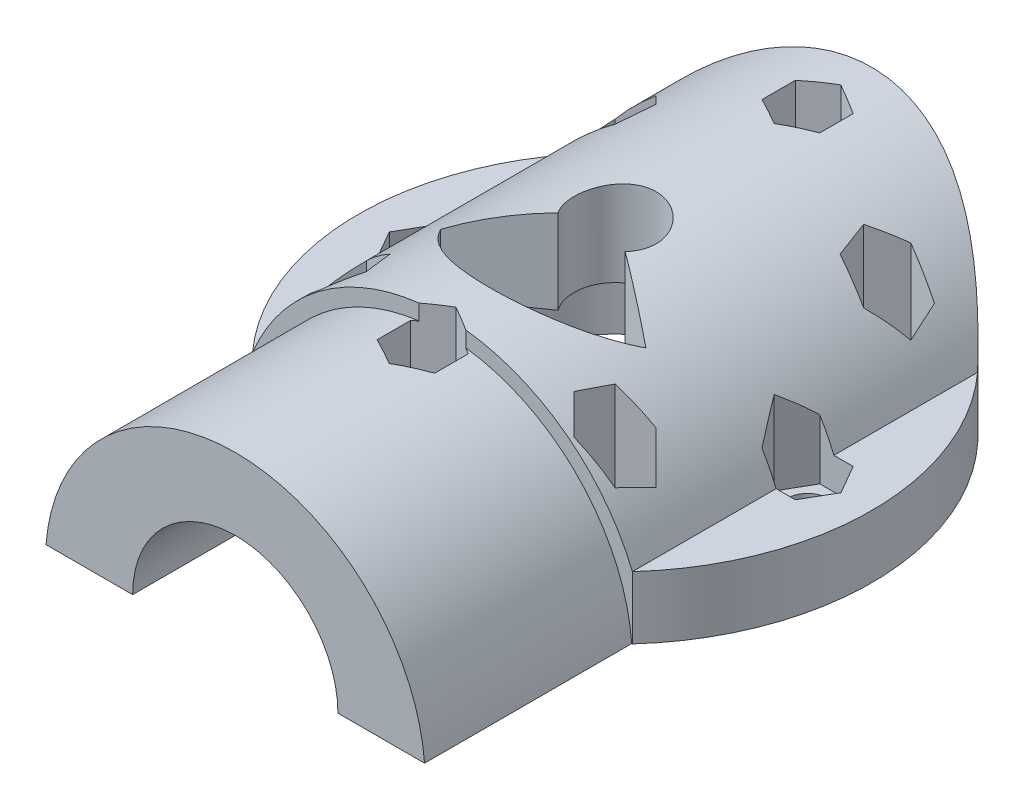
SolidWorks part; units mm, degrees
ref_plane "前视基准面" through (0, 0, 0) normal (0, 0, 1) x (1, 0, 0)
ref_plane "上视基准面" through (0, 0, 0) normal (0, 1, 0) x (1, 0, 0)
ref_plane "右视基准面" through (0, 0, 0) normal (1, 0, 0) x (0, 0, -1)
other "Configuration Table"
sketch "草图1" plane through (0, 0, 0) normal (0, 1, 0) x (1, 0, 0)
  circle A0 centre (0, 0) radius 12
  circle A1 centre (0, 0) radius 25
  dimension "D1" = 24
  dimension "D2" = 50
extrude "凸台-拉伸1" add sketch "草图1" along normal blind 10
sketch "草图2" plane through (0, 10, 0) normal (0, 1, 0) x (1, 0, 0)
  circle A0 centre (0, 0) radius 25
  circle A1 centre (0, 0) radius 4
  circle A2 centre (0, 0) radius 25 construction
  dimension "D1" = 8
extrude "凸台-拉伸2" add sketch "草图2" along normal blind 10
ref_plane "基准面1" through (0, 0, 12) normal (0, 0, 1) x (1, 0, 0)
sketch "草图5" plane through (0, 0, 12) normal (0, 0, 1) x (1, 0, 0)
  line L4 (-18.5, 20) -> (-18.5, 0)
  line L5 (25, 20) -> (-25, 20) construction
  line L6 (-25, 0) -> (25, 0) construction
  line L7 (-18.5, 0) -> (18.5, 0)
  line L8 (18.5, 0) -> (18.5, 20)
  line L9 (18.5, 20) -> (-18.5, 20)
  line L10 (0, -1000) -> (0, 49000) construction
  point P15 (0, 0)
  dimension "D1" = 37
extrude "凸台-拉伸3" add sketch "草图5" along normal blind 25
sketch "草图6" plane through (0, 0, 37) normal (0, 0, 1) x (1, 0, 0)
  line L0 (0, -1.5) -> (0, 0) construction
  line L1 (-18.4906, -0.9095) -> (-28.9864, -0.9095)
  line L2 (-28.9864, -0.9095) -> (-28.9864, 31.8558)
  line L3 (-28.9864, 31.8558) -> (34.6856, 31.8558)
  line L4 (34.6856, 31.8558) -> (34.6856, -1.6109)
  line L5 (34.6856, -1.6109) -> (18.4997, -1.6109)
  arc A0 (-18.4906, -0.9095) -> (18.4997, -1.6109) centre (0, -1.5) cw
  dimension "D1" = 18.5
  dimension "D2" = 1.5
extrude "切除-拉伸1" cut sketch "草图6" against normal up to vertex (20.1848 mm away)
sketch "草图8" plane through (0, 0, 0) normal (0, -1, 0) x (1, 0, 0)
  line L0 (-1000, 0) -> (49000, 0) construction
  line L1 (0, -1000) -> (0, 49000) construction
  line L2 (-707.1068, -707.1068) -> (34648.2323, 34648.2323) construction
  circle A0 centre (0, 0) radius 18.75 construction
  circle A1 centre (18.75, 0) radius 2
  circle A2 centre (13.2583, 13.2583) radius 2
  circle A3 centre (0, 18.75) radius 2
  circle A4 centre (-18.75, 0) radius 2
  circle A5 centre (-13.2583, 13.2583) radius 2
  circle A6 centre (13.2583, -13.2583) radius 2
  circle A7 centre (0, -18.75) radius 2
  circle A8 centre (-13.2583, -13.2583) radius 2
  dimension "D2" = 37.5
  dimension "D3" = 4
  dimension "D4" = 4
  dimension "D1" = 45
extrude "切除-拉伸2" cut sketch "草图8" against normal through all
sketch "草图9" plane through (0, 0, 0) normal (0, 1, 0) x (1, 0, 0)
  line L0 (0, 0) -> (10.5937, 25.5754)
  line L1 (10.5937, 25.5754) -> (-10.5937, 25.5754)
  line L2 (-10.5937, 25.5754) -> (0, 0)
  line L3 (0, 25.5754) -> (0, 0) construction
  dimension "D1" = 22.5
extrude "切除-拉伸4" cut sketch "草图9" along normal up to surface (10 mm away) up to face at (0, 10, 4)
sketch "草图10" plane through (0, 0, 37) normal (0, 0, 1) x (1, 0, 0)
  line L0 (0, 0) -> (0, -1.5) construction
  line L1 (-18.4391, 0) -> (18.4391, 0) construction
  line L2 (-18.5, 6.0993) -> (-25, 6.0993)
  line L3 (-25, 20) -> (-25, 0) construction
  line L4 (-25, 6.0993) -> (-25, 20)
  line L5 (-25, 20) -> (25, 20)
  line L6 (25, 20) -> (25, 6.0993)
  line L7 (25, 0) -> (25, 20) construction
  line L8 (25, 6.0993) -> (18.5, 6.0993)
  line L11 (-18.5, 20) -> (-18.5, 0) construction
  line L12 (18.5, 0) -> (18.5, 20) construction
  arc A0 (18.5, 6.0993) -> (-18.5, 6.0993) centre (0, -1.5) ccw
  dimension "D2" = 20
  dimension "D1" = 1.5
extrude "切除-拉伸5" cut sketch "草图10" against normal through all
ref_plane "基准面2" through (0, 18.5, 0) normal (0, 1, 0) x (1, 0, 0)
sketch "草图11" plane through (0, 18.5, 0) normal (0, 1, 0) x (1, 0, 0)
  line L0 (-1000.0592, 0) -> (48999.9408, 0) construction
  line L1 (0, -1000) -> (0, 49000) construction
  line L2 (-707.1068, -707.1068) -> (34648.2323, 34648.2323) construction
  line L3 (0, -15.5) -> (-2.8146, -17.125)
  line L4 (-2.8146, -17.125) -> (-2.8146, -20.375)
  line L5 (-2.8146, -20.375) -> (0, -22)
  line L6 (0, -22) -> (2.8146, -20.375)
  line L7 (2.8146, -20.375) -> (2.8146, -17.125)
  line L8 (2.8146, -17.125) -> (0, -15.5)
  line L9 (-382.6834, -923.8795) -> (18751.4882, 45270.0971) construction
  line L10 (0, -18.75) -> (-2.8146, -17.125) construction
  line L11 (-14.0994, -10.119) -> (-10.9602, -10.9602)
  line L12 (-16.3975, -12.4171) -> (-14.0994, -10.119)
  line L13 (-15.5563, -15.5563) -> (-16.3975, -12.4171)
  line L14 (-12.4171, -16.3975) -> (-15.5563, -15.5563)
  line L15 (-10.119, -14.0994) -> (-12.4171, -16.3975)
  line L16 (-10.9602, -10.9602) -> (-10.119, -14.0994)
  line L17 (10.9602, -10.9602) -> (10.119, -14.0994)
  line L18 (10.119, -14.0994) -> (12.4171, -16.3975)
  line L19 (12.4171, -16.3975) -> (15.5563, -15.5563)
  line L20 (15.5563, -15.5563) -> (16.3975, -12.4171)
  line L21 (16.3975, -12.4171) -> (14.0994, -10.119)
  line L22 (14.0994, -10.119) -> (10.9602, -10.9602)
  line L23 (-10.119, 14.0994) -> (-10.9602, 10.9602)
  line L24 (-12.4171, 16.3975) -> (-10.119, 14.0994)
  line L25 (-15.5563, 15.5563) -> (-12.4171, 16.3975)
  line L26 (-16.3975, 12.4171) -> (-15.5563, 15.5563)
  line L27 (-14.0994, 10.119) -> (-16.3975, 12.4171)
  line L28 (-10.9602, 10.9602) -> (-14.0994, 10.119)
  line L29 (-17.125, 2.8146) -> (-15.5, 0)
  line L30 (-20.375, 2.8146) -> (-17.125, 2.8146)
  line L31 (-22, 0) -> (-20.375, 2.8146)
  line L32 (-20.375, -2.8146) -> (-22, 0)
  line L33 (-17.125, -2.8146) -> (-20.375, -2.8146)
  line L34 (-15.5, 0) -> (-17.125, -2.8146)
  line L35 (10.9602, 10.9602) -> (14.0994, 10.119)
  line L36 (14.0994, 10.119) -> (16.3975, 12.4171)
  line L37 (16.3975, 12.4171) -> (15.5563, 15.5563)
  line L38 (15.5563, 15.5563) -> (12.4171, 16.3975)
  line L39 (12.4171, 16.3975) -> (10.119, 14.0994)
  line L40 (10.119, 14.0994) -> (10.9602, 10.9602)
  line L41 (15.5, 0) -> (17.125, -2.8146)
  line L42 (17.125, -2.8146) -> (20.375, -2.8146)
  line L43 (20.375, -2.8146) -> (22, 0)
  line L44 (22, 0) -> (20.375, 2.8146)
  line L45 (20.375, 2.8146) -> (17.125, 2.8146)
  line L46 (17.125, 2.8146) -> (15.5, 0)
  line L47 (2.8146, 17.125) -> (0, 15.5)
  line L48 (2.8146, 20.375) -> (2.8146, 17.125)
  line L49 (0, 22) -> (2.8146, 20.375)
  line L50 (-2.8146, 20.375) -> (0, 22)
  line L51 (-2.8146, 17.125) -> (-2.8146, 20.375)
  line L52 (0, 15.5) -> (-2.8146, 17.125)
  circle A9 centre (0, 0) radius 18.75 construction
  dimension "D1" = 45
  dimension "D2" = 120
  dimension "D3" = 3.25
  dimension "D4" = 22.5
  dimension "D5" = 60
extrude "切除-拉伸6" cut sketch "草图11" against normal offset from surface (15.5 mm away) 3 up to face at (-13.2583, 0, -15.2583)
sketch "草图12" plane through (0, 0, 37) normal (0, 0, 1) x (1, 0, 0)
  line L0 (-18.4391, 0) -> (18.4391, 0) construction
  circle A0 centre (0, 0) radius 10
  dimension "D1" = 20
extrude "切除-拉伸7" cut sketch "草图12" against normal blind 30
sketch "草图13" plane through (0, 10, 0) normal (0, -1, 0) x (1, 0, 0)
  line L0 (0, 0) -> (-10, 7)
  line L1 (0, 0) -> (10, 7)
  arc A0 (-10, 7) -> (10, 7) centre (0, 0) cw
  point P7 (0, 0)
extrude "切除-拉伸8" cut sketch "草图13" against normal through all both and the other way through all contours L0 A0 L1
